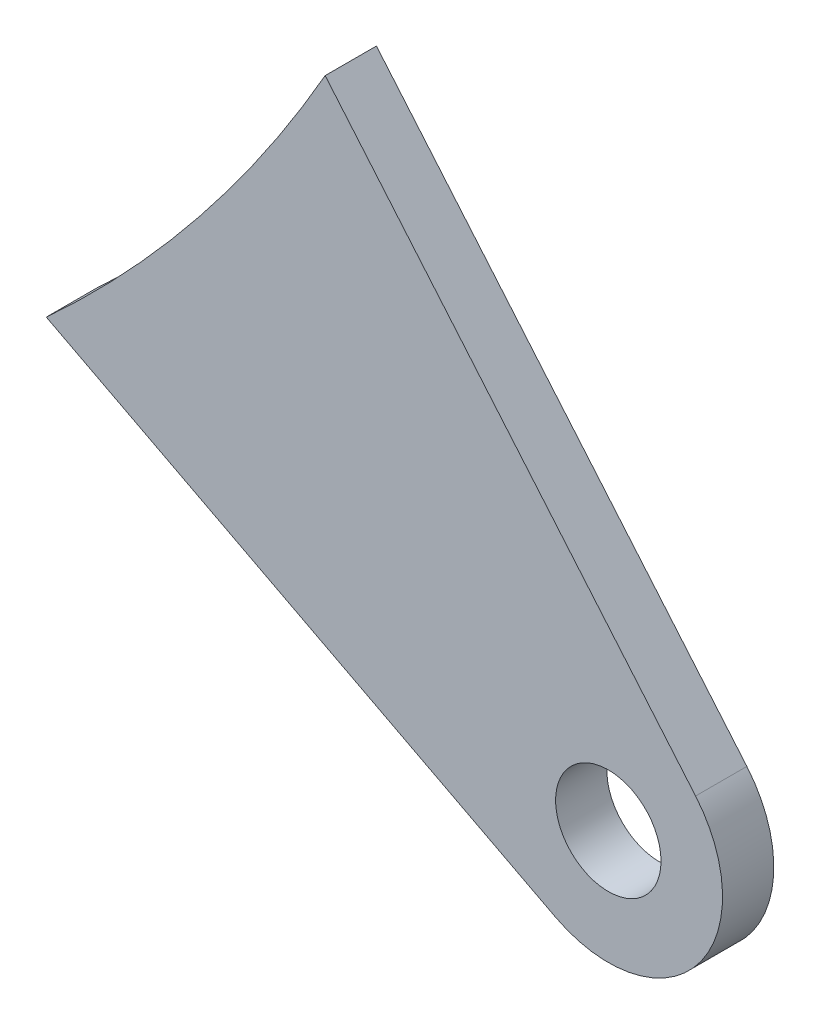
SolidWorks part; units mm, degrees
ref_plane "Front Plane" through (0, 0, 0) normal (0, 0, 1) x (1, 0, 0)
ref_plane "Top Plane" through (0, 0, 0) normal (0, 1, 0) x (1, 0, 0)
ref_plane "Right Plane" through (0, 0, 0) normal (1, 0, 0) x (0, 0, -1)
sketch "Sketch1" plane through (0, 0, 0) normal (0, 0, 1) x (1, 0, 0)
  line L0 (54.0468, -66.0558) -> (85.5894, -82.4747)
  line L1 (71.3178, -44.467) -> (94.2603, -71.6361)
  arc A0 (85.5894, -82.4747) -> (94.2603, -71.6361) centre (88.8556, -76.2) ccw
  circle A1 centre (88.8556, -76.2) radius 3.2639
  arc A2 (54.0468, -66.0558) -> (71.3178, -44.467) centre (-6.3945, 0) ccw
extrude "Boss-Extrude1" add sketch "Sketch1" along normal blind 3.175
